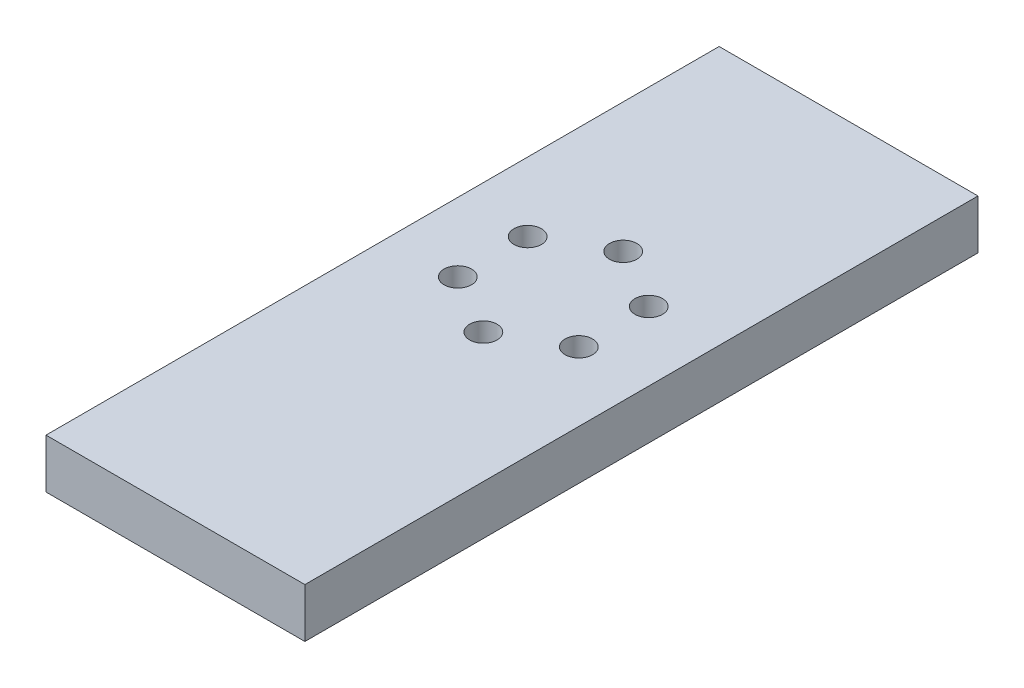
SolidWorks part; units mm, degrees
ref_plane "Front Plane" through (0, 0, 0) normal (0, 0, 1) x (1, 0, 0)
ref_plane "Top Plane" through (0, 0, 0) normal (0, 1, 0) x (1, 0, 0)
ref_plane "Right Plane" through (0, 0, 0) normal (1, 0, 0) x (0, 0, -1)
sketch "Sketch1" plane through (0, 0, 0) normal (0, 1, 0) x (1, 0, 0)
  line L1 (-25, -65) -> (25, -65)
  line L2 (-25, -65) -> (-25, 65)
  line L3 (-25, 65) -> (25, 65)
  line L4 (25, -65) -> (25, 65)
  line L5 (-25, -65) -> (25, 65) construction
  line L6 (-25, 65) -> (25, -65) construction
  point P0 (0, 0)
  dimension "D1" = 50
  dimension "D2" = 130
extrude "Boss-Extrude1" add sketch "Sketch1" along normal blind 9.525
sketch "Sketch2" plane through (0, 0, 0) normal (0, -1, 0) x (1, 0, 0)
  circle A0 centre (16.67, 60.2375) radius 2 construction
  circle A1 centre (0, 60.2375) radius 2 construction
  circle A2 centre (-16.67, 60.2375) radius 2 construction
  circle A3 centre (16.67, 35.7) radius 1.65 construction
  circle A4 centre (0, 35.7) radius 1.65 construction
  circle A5 centre (-16.67, 35.7) radius 1.65 construction
  circle A6 centre (-16.67, -60.2375) radius 2 construction
  circle A7 centre (0, -60.2375) radius 2 construction
  circle A8 centre (16.67, -60.2375) radius 2 construction
  circle A9 centre (16.67, 60.2375) radius 2
  circle A10 centre (0, 60.2375) radius 2
  circle A11 centre (-16.67, 60.2375) radius 2
  circle A12 centre (16.67, 35.7) radius 1.65
  circle A13 centre (0, 35.7) radius 1.65
  circle A14 centre (-16.67, 35.7) radius 1.65
  circle A15 centre (-16.67, -60.2375) radius 2
  circle A16 centre (0, -60.2375) radius 2
  circle A17 centre (16.67, -60.2375) radius 2
  point P28 (-16.67, -60.2375)
  point P29 (0, -60.2375)
  point P30 (16.67, -60.2375)
  point P31 (16.67, 35.7)
  point P32 (0, 35.7)
  point P33 (-16.67, 35.7)
  point P34 (16.67, 60.2375)
  point P35 (0, 60.2375)
  point P36 (-16.67, 60.2375)
hole_wizard "Ø4.0mm Dowel Hole1" positions "Sketch2" profile "Sketch3" hole size "Ø4.0" standard "ANSI Metric"
sketch "Sketch3" plane through (-16.67, 0, 60.2375) normal (1, 0, 0) x (0, 0, -1)
  line L0 (0, 0) -> (0, 4.4017)
  line L1 (0, 4.4017) -> (2, 3.2)
  line L2 (2, 3.2) -> (2, 0)
  line L5 (2, 0) -> (0, 0)
  line L10 (0, 4.4017) -> (-2, 3.2) construction
  line L11 (0, -6.35) -> (0, 107.95) construction
  dimension "Hole Dia." = 4
  dimension "Hole Depth" = 3.2
  dimension "Drill Angle" = 118
sketch "Sketch4" plane through (0, 9.525, 0) normal (0, 1, 0) x (1, 0, 0)
  line L0 (25, 65) -> (-25, 65) construction
  circle A0 centre (0, 7.97) radius 13.5 construction
  point P4 (0, 21.47)
  point P7 (11.6913, 14.72)
  point P8 (11.6913, 1.22)
  point P9 (0, -5.53)
  point P10 (-11.6913, 1.22)
  point P11 (-11.6913, 14.72)
  point P12 (0, 7.97)
  dimension "D1" = 27
  dimension "D2" = 57.03
  dimension "D3" = 6
hole_wizard "M5 Clearance Hole1" positions "Sketch4" profile "Sketch5" hole size "M5" standard "ANSI Metric"
sketch "Sketch5" plane through (-11.6913, 9.525, -14.72) normal (1, 0, 0) x (0, 0, 1)
  line L0 (0, 0) -> (0, 9.525)
  line L1 (0, 9.525) -> (2.65, 9.525)
  line L2 (2.65, 9.525) -> (2.65, 0)
  line L5 (2.65, 0) -> (0, 0)
  line L11 (0, -6.35) -> (0, 107.95) construction
  dimension "Thru Hole Dia." = 5.3
  dimension "Thru Hole Depth" = 9.525
